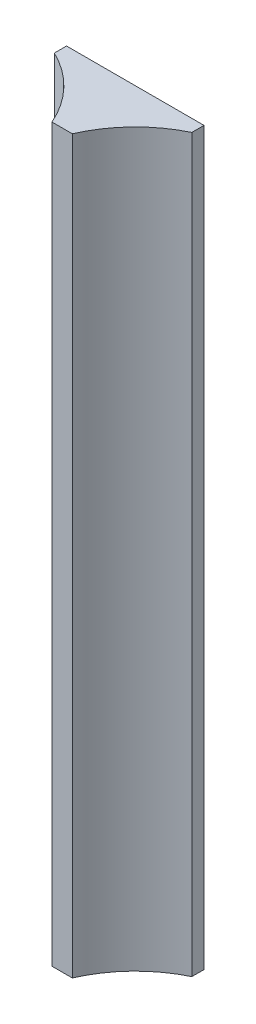
SolidWorks part; units mm, degrees
ref_plane "Front" through (0, 0, 0) normal (0, 0, 1) x (1, 0, 0)
ref_plane "Top" through (0, 0, 0) normal (0, 1, 0) x (1, 0, 0)
ref_plane "Right" through (0, 0, 0) normal (1, 0, 0) x (0, 0, -1)
sketch "Sketch1" plane through (0, 0, 0) normal (0, 1, 0) x (1, 0, 0)
  line L0 (-0.8348, 0) -> (0.8348, 0)
  line L1 (5.6411, 5) -> (5.6411, 6)
  line L2 (5.6411, 6) -> (-5.6411, 6)
  line L3 (-5.6411, 6) -> (-5.6411, 5)
  arc A0 (0.8348, 0) -> (5.6411, 5) centre (10, -4) cw
  arc A1 (-5.6411, 5) -> (-0.8348, 0) centre (-10, -4) cw
  point P9 (0, 6)
  point P10 (0, 0)
  dimension "D1" = 10
  dimension "D6" = 6
  dimension "D2" = 20
  dimension "D3" = 10
  dimension "D4" = 1
extrude "Boss-Extrude1" add sketch "Sketch1" along normal blind 60
sketch "Sketch3" plane through (0, 0, -6) normal (0, 0, -1) x (-1, 0, 0)
  line L0 (0, 0) -> (0, 60) construction
  line L1 (-5.6411, 0) -> (5.6411, 0) construction
  line L2 (-5.6411, 60) -> (5.6411, 60) construction
  point P6 (0, 45)
  point P7 (0, 15)
  dimension "D1" = 15
  dimension "D2" = 15
